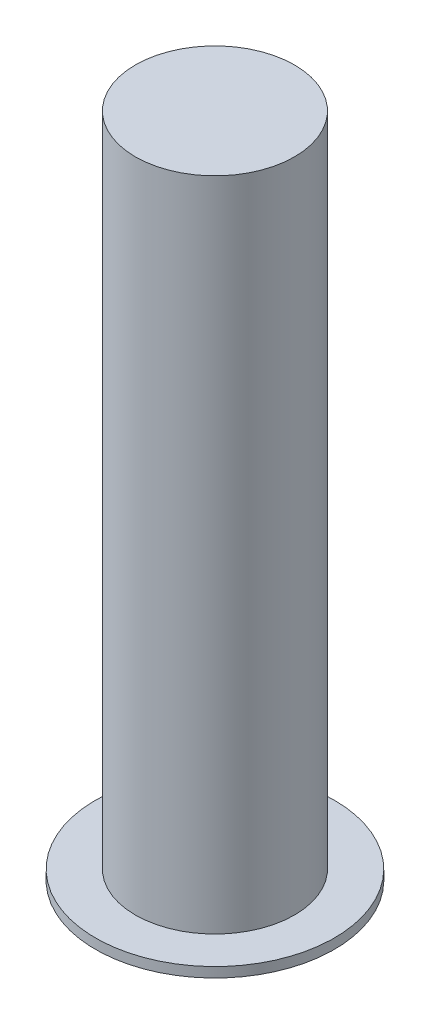
SolidWorks part; units mm, degrees
ref_plane "Front Plane" through (0, 0, 0) normal (0, 0, 1) x (1, 0, 0)
ref_plane "Top Plane" through (0, 0, 0) normal (0, 1, 0) x (1, 0, 0)
ref_plane "Right Plane" through (0, 0, 0) normal (1, 0, 0) x (0, 0, -1)
sketch "Sketch1" plane through (0, 0, 0) normal (0, 1, 0) x (1, 0, 0)
  circle A0 centre (0, 0) radius 4
  dimension "D1" = 8
extrude "Boss-Extrude1" add sketch "Sketch1" along normal blind 33
sketch "Sketch2" plane through (0, 0, 0) normal (0, -1, 0) x (1, 0, 0)
  circle A0 centre (0, 0) radius 6
  dimension "D1" = 12
extrude "Boss-Extrude2" add sketch "Sketch2" along normal blind 0.5
